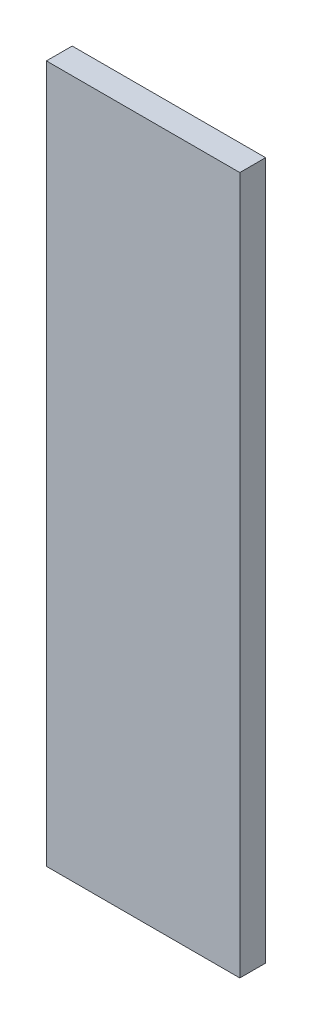
SolidWorks part; units mm, degrees
material "1060 Сплав"
ref_plane "Front" through (0, 0, 0) normal (0, 0, 1) x (1, 0, 0)
ref_plane "Top" through (0, 0, 0) normal (0, 1, 0) x (1, 0, 0)
ref_plane "Right" through (0, 0, 0) normal (1, 0, 0) x (0, 0, -1)
sketch "Эскиз1" plane through (0, 0, 0) normal (0, 0, 1) x (1, 0, 0)
  line L1 (0, 0) -> (15, 0)
  line L2 (0, 0) -> (0, 54.1)
  line L3 (0, 54.1) -> (15, 54.1)
  line L4 (15, 0) -> (15, 54.1)
  dimension "D1" = 54.1
  dimension "D2" = 15
extrude "Бобышка-Вытянуть1" add sketch "Эскиз1" along normal blind 2
